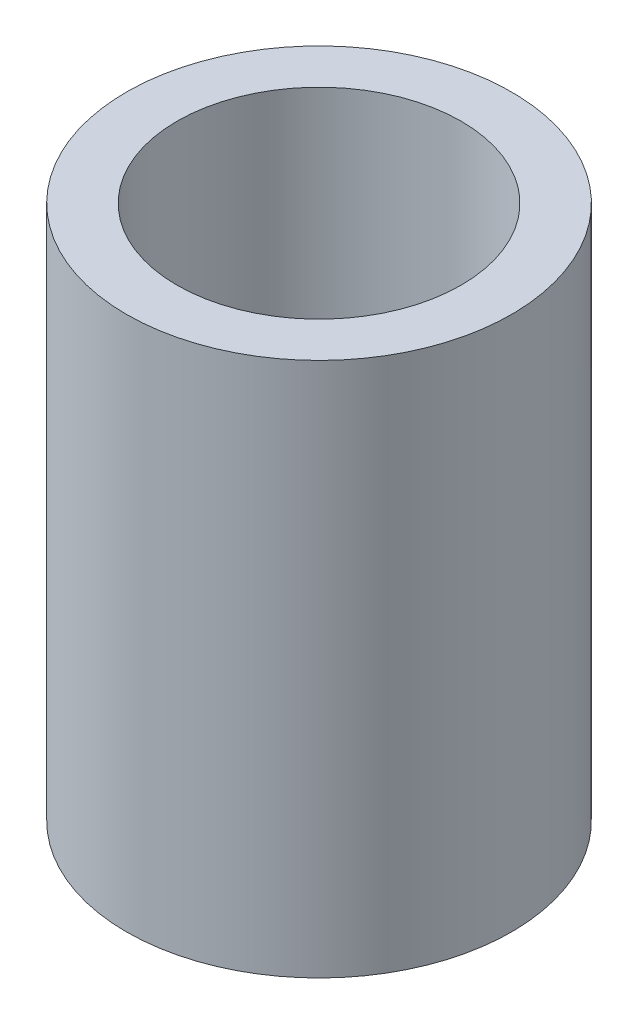
SolidWorks part; units mm, degrees
ref_plane "Front Plane" through (0, 0, 0) normal (0, 0, 1) x (1, 0, 0)
ref_plane "Top Plane" through (0, 0, 0) normal (0, 1, 0) x (1, 0, 0)
ref_plane "Right Plane" through (0, 0, 0) normal (1, 0, 0) x (0, 0, -1)
sketch "Sketch1" plane through (0, 0, 0) normal (0, 1, 0) x (1, 0, 0)
  circle A0 centre (0, 0) radius 3.3734
  circle A1 centre (0, 0) radius 4.5734
  dimension "D1" = 6.7469
  dimension "D2" = 1.2
extrude "Boss-Extrude1" add sketch "Sketch1" along normal blind 3.175
sketch "Sketch2" plane through (0, 3.175, 0) normal (0, 1, 0) x (1, 0, 0)
  circle A0 centre (0, 0) radius 3.3734 construction
  circle A1 centre (0, 0) radius 4.5734
  circle A2 centre (0, 0) radius 4.5734
  circle A3 centre (0, 0) radius 3.3734
  dimension "D1" = 0
extrude "Boss-Extrude2" add sketch "Sketch2" along normal blind 9.525
